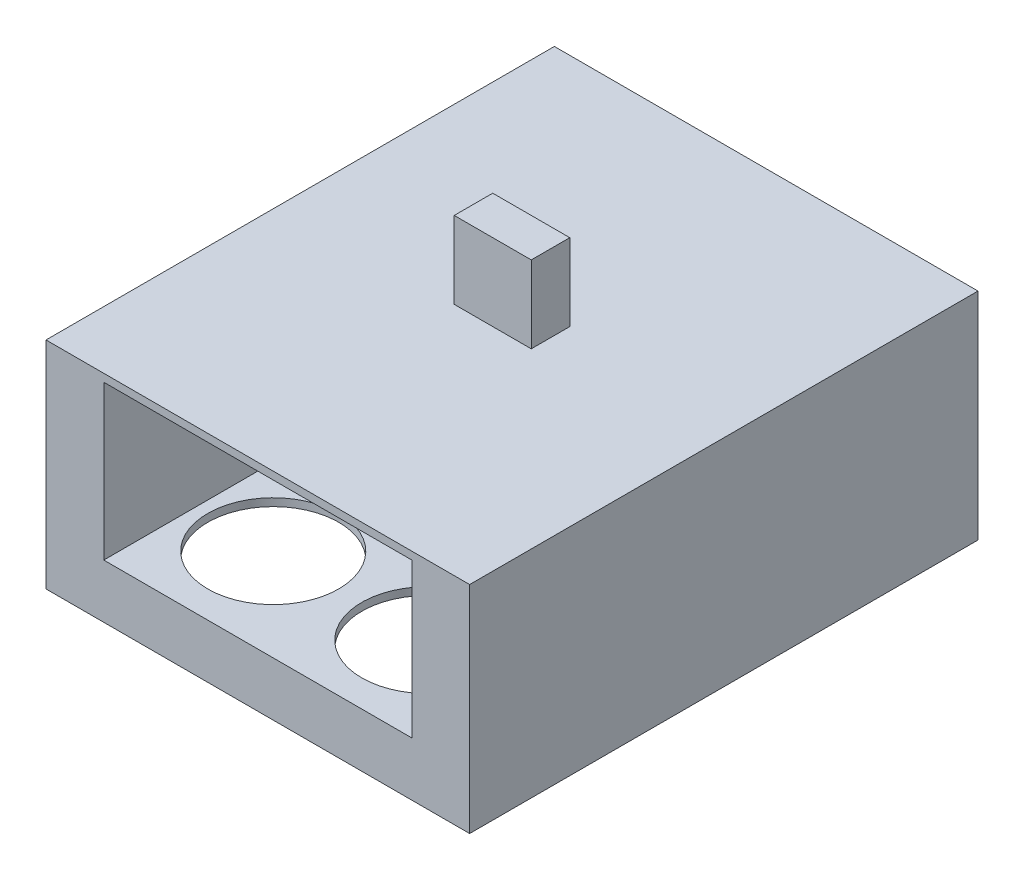
SolidWorks part; units mm, degrees
ref_plane "Front Plane" through (0, 0, 0) normal (0, 0, 1) x (1, 0, 0)
ref_plane "Top Plane" through (0, 0, 0) normal (0, 1, 0) x (1, 0, 0)
ref_plane "Right Plane" through (0, 0, 0) normal (1, 0, 0) x (0, 0, -1)
sketch "Sketch1" plane through (0, 0, 0) normal (0, 0, 1) x (1, 0, 0)
  line L2 (55, 0) -> (-55, 0) construction
  line L4 (34.925, 0) -> (34.925, 6.35)
  line L5 (34.925, 6.35) -> (-34.925, 6.35)
  line L6 (-34.925, 6.35) -> (-34.925, 0)
  line L9 (0, 3.81) -> (0, 0) construction
  line L10 (-34.925, 0) -> (34.925, 0)
  point P3 (0, 3.81)
  dimension "D5" = 69.85
extrude "Boss-Extrude1" add sketch "Sketch1" along normal mid plane 83.82
shell "Shell1" thickness 2.54
sketch "Sketch2" plane through (0, 6.35, 0) normal (0, 1, 0) x (1, 0, 0)
  line L1 (-34.925, -41.91) -> (34.925, -41.91)
  line L2 (-34.925, -41.91) -> (-34.925, 41.91)
  line L3 (-34.925, 41.91) -> (34.925, 41.91)
  line L4 (34.925, -41.91) -> (34.925, 41.91)
extrude "Boss-Extrude2" add sketch "Sketch2" along normal blind 25.4
sketch "Sketch5" plane through (0, 0, 0) normal (0, 0, 1) x (1, 0, 0)
  line L0 (-6.35, 31.75) -> (6.35, 31.75)
  line L1 (6.35, 31.75) -> (6.35, 44.45)
  line L2 (6.35, 44.45) -> (-6.35, 44.45)
  line L3 (-6.35, 44.45) -> (-6.35, 31.75)
  line L4 (0, 0) -> (0, 31.75) construction
  line L5 (-34.925, 31.75) -> (34.925, 31.75) construction
  point P3 (0, 31.75)
extrude "Boss-Extrude5" add sketch "Sketch5" along normal mid plane 6.35
sketch "Sketch6" plane through (0, 0, 41.91) normal (0, 0, 1) x (1, 0, 0)
  line L0 (0, 0) -> (0, 5.08) construction
  line L1 (-25.4, 5.08) -> (25.4, 5.08)
  line L2 (25.4, 5.08) -> (25.4, 30.48)
  line L3 (25.4, 30.48) -> (-25.4, 30.48)
  line L4 (-25.4, 30.48) -> (-25.4, 5.08)
  point P7 (0, 5.08)
  dimension "D1" = 5.08
  dimension "D2" = 25.4
  dimension "D3" = 50.8
extrude "Cut-Extrude1" cut sketch "Sketch6" against normal blind 30.48
sketch "Sketch7" plane through (0, 5.08, 0) normal (0, 1, 0) x (1, 0, 0)
  line L0 (0, -41.91) -> (0, -11.43) construction
  line L3 (-12.7, -26.67) -> (12.7, -26.67) construction
  line L4 (-25.4, -41.91) -> (25.4, -41.91) construction
  line L5 (-25.4, -11.43) -> (25.4, -11.43) construction
  circle A0 centre (-12.7, -26.67) radius 10.795
  circle A1 centre (12.7, -26.67) radius 10.795
  point P9 (0, -26.67)
  point P12 (0, -26.67)
  dimension "D2" = 21.59
  dimension "D3" = 21.59
  dimension "D1" = 25.4
extrude "Cut-Extrude2" cut sketch "Sketch7" against normal up to next
sketch "Sketch8" plane through (0, 0, 0) normal (0, -1, 0) x (1, 0, 0)
  line L1 (-34.925, -41.91) -> (34.925, -41.91)
  line L2 (-34.925, -41.91) -> (-34.925, 41.91)
  line L3 (-34.925, 41.91) -> (34.925, 41.91)
  line L4 (34.925, -41.91) -> (34.925, 41.91)
  line L5 (-32.385, -39.37) -> (32.385, -39.37)
  line L6 (-32.385, -39.37) -> (-32.385, 39.37)
  line L7 (-32.385, 39.37) -> (32.385, 39.37)
  line L8 (32.385, -39.37) -> (32.385, 39.37)
extrude "Boss-Extrude6" add sketch "Sketch8" along normal blind 3.81
equation "\"Lid L\"=3.3"
equation "\"Lid W\"= 2.75"
equation "\"Lid H\"= .25"
equation "\"D1@Boss-Extrude1\"=\"Lid L\""
equation "\"D5@Sketch1\"=\"Lid W\""
equation "\"D1@Sketch1\"=\"Lid H\""
equation "\"Walls\"= .1"
equation "\"D1@Shell1\"=\"Walls\""
equation "\"Handle L\"= .5"
equation "\"Handle W\"=1"
equation "\"Handle H\"= .5"
equation "\"D1@Boss-Extrude2\"=\"Handle W\""
